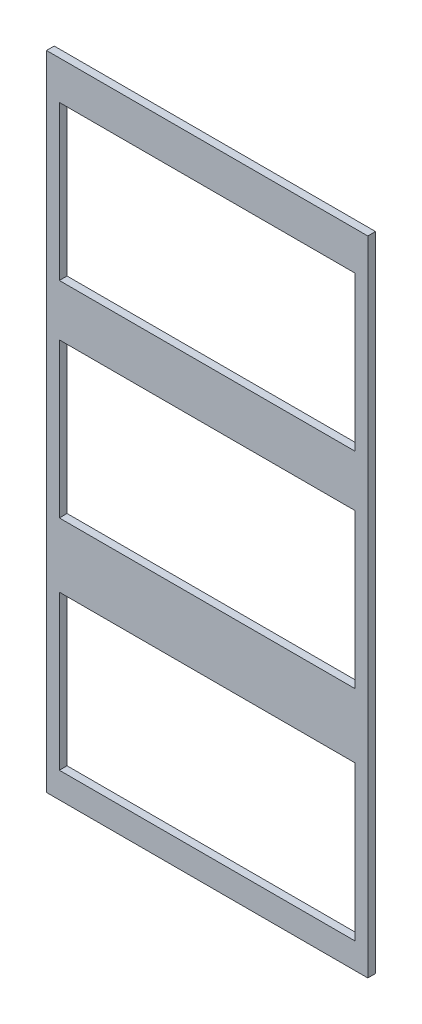
SolidWorks part; units mm, degrees
ref_plane "Plano frontal" through (0, 0, 0) normal (0, 0, 1) x (1, 0, 0)
ref_plane "Plano superior" through (0, 0, 0) normal (0, 1, 0) x (1, 0, 0)
ref_plane "Plano direito" through (0, 0, 0) normal (1, 0, 0) x (0, 0, -1)
sketch "Esboço1" plane through (0, 0, 0) normal (0, 0, 1) x (1, 0, 0)
  line L1 (0, 0) -> (250, 0)
  line L2 (0, 0) -> (0, -500)
  line L3 (0, -500) -> (250, -500)
  line L4 (250, 0) -> (250, -500)
extrude "Ressalto-extrusão1" add sketch "Esboço1" along normal blind 6
sketch "Esboço2" plane through (0, 0, 0) normal (0, 0, -1) x (-1, 0, 0)
  line L0 (-220.8753, -51.4243) -> (-33.6653, -51.4243)
  line L1 (-250, -500) -> (-250, 0) construction
  line L2 (-240, -30) -> (-10, -30)
  line L3 (-240, -30) -> (-240, -150)
  line L4 (-240, -150) -> (-10, -150)
  line L5 (-10, -30) -> (-10, -150)
  line L6 (0, 0) -> (0, -500) construction
  line L7 (-250, 0) -> (0, 0) construction
  line L9 (-240, -190) -> (-10, -190)
  line L10 (-240, -190) -> (-240, -310)
  line L11 (-240, -310) -> (-10, -310)
  line L12 (-10, -190) -> (-10, -310)
  line L13 (-240, -360) -> (-10, -360)
  line L14 (-240, -360) -> (-240, -480)
  line L15 (-240, -480) -> (-10, -480)
  line L16 (-10, -360) -> (-10, -480)
  dimension "D1" = 10
  dimension "D2" = 10
  dimension "D3" = 30
  dimension "D4" = 120
  dimension "D5" = 40
  dimension "D6" = 120
  dimension "D7" = 120
  dimension "D8" = 50
extrude "Corte-extrusão1" cut sketch "Esboço2" against normal through all
